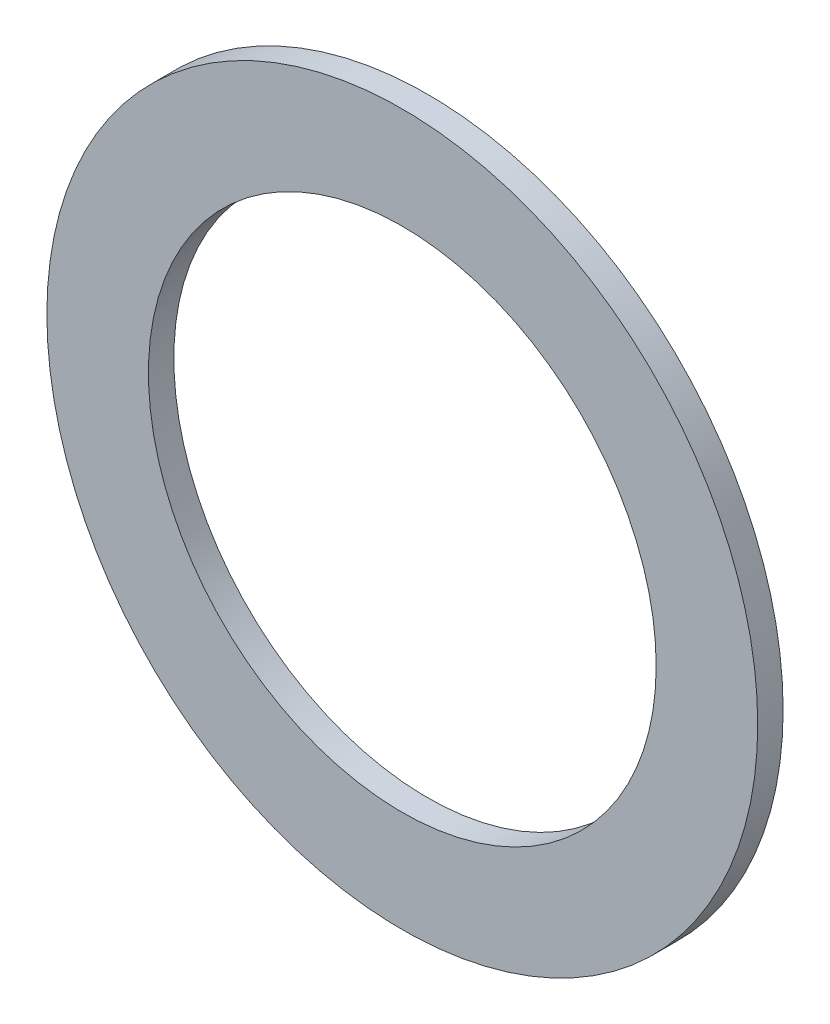
SolidWorks part; units mm, degrees
ref_plane "前视基准面" through (0, 0, 0) normal (0, 0, 1) x (1, 0, 0)
ref_plane "上视基准面" through (0, 0, 0) normal (0, 1, 0) x (1, 0, 0)
ref_plane "右视基准面" through (0, 0, 0) normal (1, 0, 0) x (0, 0, -1)
sketch "草图1" plane through (0, 0, 0) normal (0, 0, 1) x (1, 0, 0)
  circle A0 centre (0, 0) radius 7
  circle A1 centre (0, 0) radius 5
  dimension "D1" = 14
  dimension "D2" = 10
extrude "凸台-拉伸1" add sketch "草图1" along normal blind 0.5
